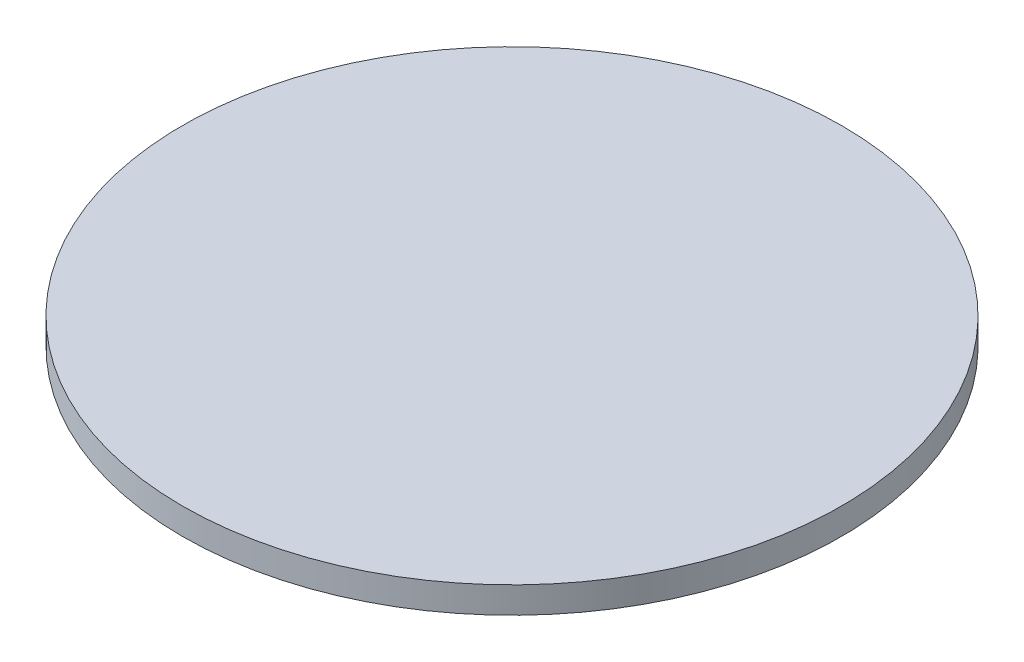
SolidWorks part; units mm, degrees
ref_plane "Front Plane" through (0, 0, 0) normal (0, 0, 1) x (1, 0, 0)
ref_plane "Top Plane" through (0, 0, 0) normal (0, 1, 0) x (1, 0, 0)
ref_plane "Right Plane" through (0, 0, 0) normal (1, 0, 0) x (0, 0, -1)
sketch "Sketch1" plane through (0, 0, 0) normal (0, 1, 0) x (1, 0, 0)
  circle A0 centre (0, 0) radius 5
  dimension "D1" = 10
extrude "Boss-Extrude1" add sketch "Sketch1" along normal blind 0.4
